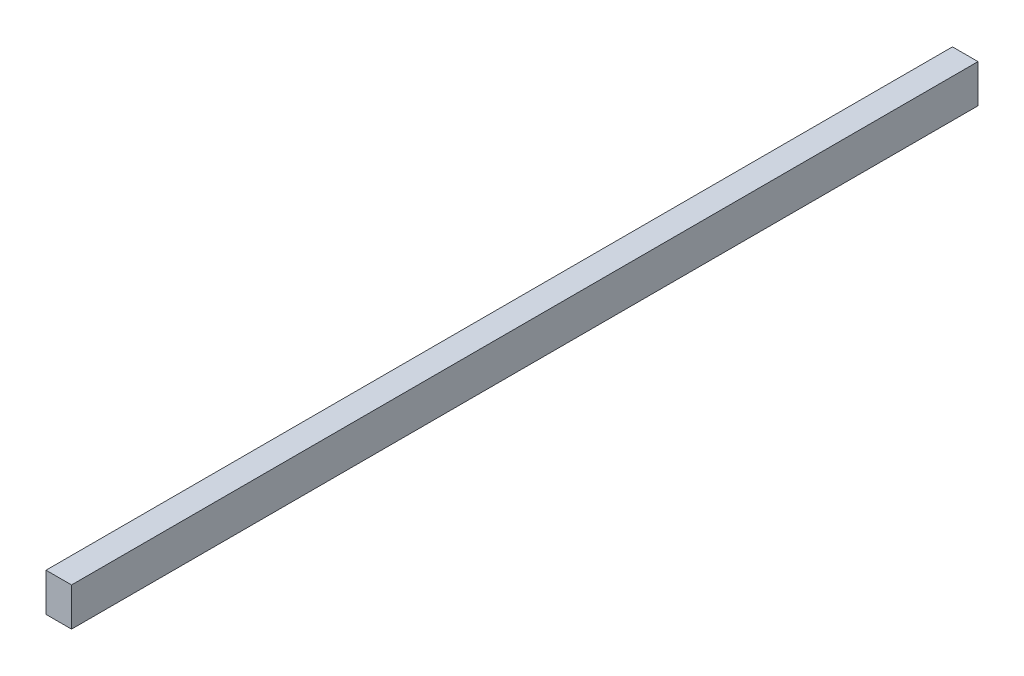
SolidWorks part; units mm, degrees
ref_plane "Front Plane" through (0, 0, 0) normal (0, 0, 1) x (1, 0, 0)
ref_plane "Top Plane" through (0, 0, 0) normal (0, 1, 0) x (1, 0, 0)
ref_plane "Right Plane" through (0, 0, 0) normal (1, 0, 0) x (0, 0, -1)
sketch "Sketch1" plane through (0, 0, 0) normal (1, 0, 0) x (0, 0, -1)
  line L1 (0, 0) -> (426, 0)
  line L2 (0, 0) -> (0, 18)
  line L3 (0, 18) -> (426, 18)
  line L4 (426, 0) -> (426, 18)
  dimension "D1" = 426
  dimension "D2" = 18
extrude "Boss-Extrude1" add sketch "Sketch1" along normal blind 12
